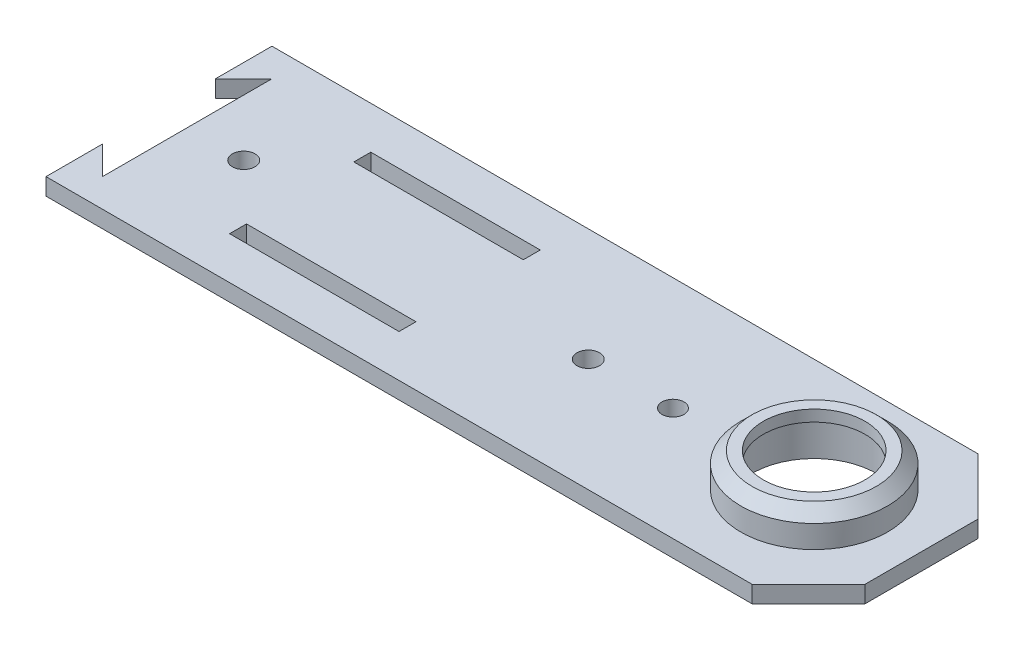
SolidWorks part; units mm, degrees
ref_plane "Alzado" through (0, 0, 0) normal (0, 0, 1) x (1, 0, 0)
ref_plane "Planta" through (0, 0, 0) normal (0, 1, 0) x (1, 0, 0)
ref_plane "Vista lateral" through (0, 0, 0) normal (1, 0, 0) x (0, 0, -1)
sketch "Croquis1" plane through (0, 0, 0) normal (0, 1, 0) x (1, 0, 0)
  line L0 (-67.5, 10) -> (-62.5, 15)
  line L1 (-67.5, -20) -> (67.5, -20)
  line L2 (-67.5, -20) -> (-67.5, -10)
  line L3 (-67.5, 20) -> (67.5, 20)
  line L4 (67.5, -20) -> (67.5, 20)
  line L5 (-67.5, -20) -> (67.5, 20) construction
  line L6 (-67.5, 20) -> (67.5, -20) construction
  line L7 (-62.5, 15) -> (-62.5, -15)
  line L8 (-62.5, -15) -> (-67.5, -10)
  line L9 (-67.5, 10) -> (-67.5, 20)
  line L11 (-42.5, 9.5) -> (-12.5, 9.5)
  line L12 (-42.5, 9.5) -> (-42.5, 12.5)
  line L13 (-42.5, 12.5) -> (-12.5, 12.5)
  line L14 (-12.5, 9.5) -> (-12.5, 12.5)
  line L15 (-42.5, 9.5) -> (-12.5, 12.5) construction
  line L16 (-42.5, 12.5) -> (-12.5, 9.5) construction
  line L17 (-42.5, -12.5) -> (-12.5, -12.5)
  line L18 (-42.5, -12.5) -> (-42.5, -9.5)
  line L19 (-42.5, -9.5) -> (-12.5, -9.5)
  line L20 (-12.5, -12.5) -> (-12.5, -9.5)
  line L21 (-42.5, -12.5) -> (-12.5, -9.5) construction
  line L22 (-42.5, -9.5) -> (-12.5, -12.5) construction
  circle A2 centre (48.5, 0) radius 11
  circle A3 centre (-52.5, 0) radius 2
  circle A4 centre (23.5, 0) radius 1.9377
  circle A5 centre (8.5, 0) radius 2
  point P0 (0, 0)
  point P8 (-62.5, 0)
  point P20 (-27.5, 11)
  point P28 (-27.5, -11)
  dimension "D6" = 15
  dimension "D7" = 22
  dimension "D11" = 10
  dimension "D12" = 4
  dimension "D1" = 40
  dimension "D2" = 135
  dimension "D3" = 45
  dimension "D4" = 20
  dimension "D5" = 30
  dimension "D8" = 30
  dimension "D9" = 3
  dimension "D10" = 40
  dimension "D13" = 12.5
  dimension "D14" = 12.5
  dimension "D15" = 19
  dimension "D16" = 25
extrude "Saliente-Extruir1" add sketch "Croquis1" along normal blind 3
sketch "Croquis2" plane through (0, 3, 0) normal (0, 1, 0) x (1, 0, 0)
  circle A0 centre (48.5, 0) radius 11
  circle A1 centre (48.5, 0) radius 13
  dimension "D1" = 2
extrude "Saliente-Extruir2" add sketch "Croquis2" along normal blind 4
sketch "Croquis3" plane through (0, 7, 0) normal (0, 1, 0) x (1, 0, 0)
  circle A0 centre (48.5, 0) radius 13
  circle A1 centre (48.5, 0) radius 9
  dimension "D1" = 18
extrude "Saliente-Extruir3" add sketch "Croquis3" along normal blind 2
chamfer "Chaflán1" distance 2 angle 45 1 edges at (48.5, 9, 13)
chamfer "Chaflán2" distance 10 angle 45 2 edges at (67.5, 1.5, -20) (67.5, 1.5, 20)
